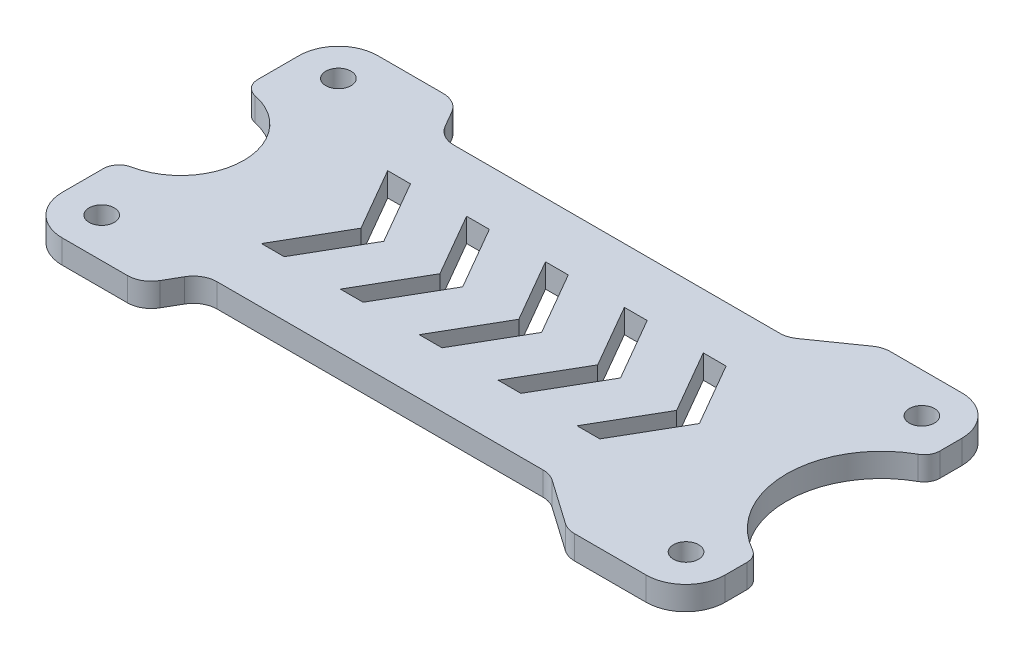
SolidWorks part; units mm, degrees
ref_plane "Front Plane" through (0, 0, 0) normal (0, 0, 1) x (1, 0, 0)
ref_plane "Top Plane" through (0, 0, 0) normal (0, 1, 0) x (1, 0, 0)
ref_plane "Right Plane" through (0, 0, 0) normal (1, 0, 0) x (0, 0, -1)
sketch "Sketch1" plane through (0, 53, 0) normal (0, 1, 0) x (1, 0, 0)
  line L8 (42, -14.9441) -> (42, 14.9441) construction
  line L9 (-37, 20) -> (37, 20)
  line L10 (-42, 15) -> (-42, -15)
  line L11 (-37, -20) -> (37, -20)
  line L12 (42, 15) -> (42, -15)
  line L13 (-42, 15) -> (-42, -15) construction
  line L14 (-3.2304, -20) -> (4.6447, -20) construction
  line L15 (-35.7279, 20) -> (-37, 20) construction
  arc A12 (37, 20) -> (42, 15) centre (37, 15) cw
  arc A13 (37, -20) -> (42, -15) centre (37, -15) ccw
  arc A14 (-42, -15) -> (-37, -20) centre (-37, -15) ccw
  arc A15 (-37, 20) -> (-42, 15) centre (-37, 15) ccw
  circle A17 centre (37, 14.9441) radius 1.6 construction
  circle A18 centre (37, 14.9441) radius 1.6
  circle A19 centre (37, -14.9441) radius 1.6 construction
  circle A20 centre (37, -14.9441) radius 1.6
  circle A21 centre (-37, -15) radius 1.6 construction
  circle A22 centre (-37, -15) radius 1.6
  circle A23 centre (-37, 15) radius 1.6 construction
  circle A24 centre (-37, 15) radius 1.6
  dimension "D1" = 0
  dimension "D5" = 5
  dimension "D2" = 0
  dimension "D3" = 0
  dimension "D4" = 0
extrude "Boss-Extrude1" add sketch "Sketch1" along normal blind 3
sketch "Sketch2" plane through (0, 56, 0) normal (0, 1, 0) x (1, 0, 0)
  line L0 (-27, 20) -> (-24.1132, 15)
  line L1 (37, 20) -> (-37, 20) construction
  line L2 (-24.1132, 15) -> (19.8593, 15)
  line L3 (19.8593, 15) -> (27, 20)
  line L4 (-27, 20) -> (27, 20)
  line L5 (42, -15) -> (42, 15) construction
  line L6 (-42, 15) -> (-42, -15) construction
  line L7 (-42, 0) -> (42, 0) construction
  line L8 (-27, -20) -> (27, -20)
  line L9 (19.8593, -15) -> (27, -20)
  line L10 (-24.1132, -15) -> (19.8593, -15)
  line L11 (-27, -20) -> (-24.1132, -15)
  line L12 (42, 11) -> (42, -11)
  line L13 (-42, 8) -> (-42, -8)
  arc A0 (42, 11) -> (42, -11) centre (46.7958, 0) ccw
  arc A1 (-42, 8) -> (-42, -8) centre (-42, 0) cw
  dimension "D8" = 12
  dimension "D9" = 8
  dimension "D1" = 35
  dimension "D2" = 60
  dimension "D3" = 5
  dimension "D4" = 15
  dimension "D5" = 15
  dimension "D6" = 11
  dimension "D7" = 11
extrude "Cut-Extrude1" cut sketch "Sketch2" against normal up to surface (3 mm away) up to face at (-37, 53, 16.6)
fillet "Fillet1" radius 3 8 edges at (19.8593, 54.5, -15) (27, 54.5, -20) (-27, 54.5, -20) (-24.1132, 54.5, -15) (-27, 54.5, 20) (-24.1132, 54.5, 15) (19.8593, 54.5, 15) (27, 54.5, 20)
sketch "Sketch3" plane through (0, 56, 0) normal (0, 1, 0) x (1, 0, 0)
  line L0 (20.8632, 0) -> (16.2444, 8) construction
  line L10 (16.2444, -8) -> (20.8632, 0) construction
  line L11 (23.75, 0) -> (19.1312, -8) construction
  line L16 (19.1312, 8) -> (23.75, 0) construction
  line L17 (20.8632, 0) -> (16.2444, 8)
  line L18 (16.2444, -8) -> (20.8632, 0)
  line L19 (23.75, 0) -> (19.1312, -8)
  line L20 (19.1312, 8) -> (23.75, 0)
  line L21 (19.1312, -8) -> (16.2444, -8) construction
  line L22 (19.1312, -8) -> (16.2444, -8)
  line L23 (16.2444, 8) -> (19.1312, 8) construction
  line L24 (16.2444, 8) -> (19.1312, 8)
  line L25 (10.8632, 0) -> (6.2444, 8)
  line L26 (6.2444, -8) -> (10.8632, 0)
  line L27 (13.75, 0) -> (9.1312, -8)
  line L28 (9.1312, 8) -> (13.75, 0)
  line L29 (9.1312, -8) -> (6.2444, -8)
  line L30 (6.2444, 8) -> (9.1312, 8)
  line L31 (0.8632, 0) -> (-3.7556, 8)
  line L32 (-3.7556, -8) -> (0.8632, 0)
  line L33 (3.75, 0) -> (-0.8688, -8)
  line L34 (-0.8688, 8) -> (3.75, 0)
  line L35 (-0.8688, -8) -> (-3.7556, -8)
  line L36 (-3.7556, 8) -> (-0.8688, 8)
  line L37 (-9.1368, 0) -> (-13.7556, 8)
  line L38 (-13.7556, -8) -> (-9.1368, 0)
  line L39 (-6.25, 0) -> (-10.8688, -8)
  line L40 (-10.8688, 8) -> (-6.25, 0)
  line L41 (-10.8688, -8) -> (-13.7556, -8)
  line L42 (-13.7556, 8) -> (-10.8688, 8)
  line L43 (-19.1368, 0) -> (-23.7556, 8)
  line L44 (-23.7556, -8) -> (-19.1368, 0)
  line L45 (-16.25, 0) -> (-20.8688, -8)
  line L46 (-20.8688, 8) -> (-16.25, 0)
  line L47 (-20.8688, -8) -> (-23.7556, -8)
  line L48 (-23.7556, 8) -> (-20.8688, 8)
  dimension "D1" = 5
extrude "Cut-Extrude2" cut sketch "Sketch3" against normal through all
fillet "Fillet2" radius 2 4 edges at (-42, 54.5, 8) (-42, 54.5, -8) (42, 54.5, -11) (42, 54.5, 11)
